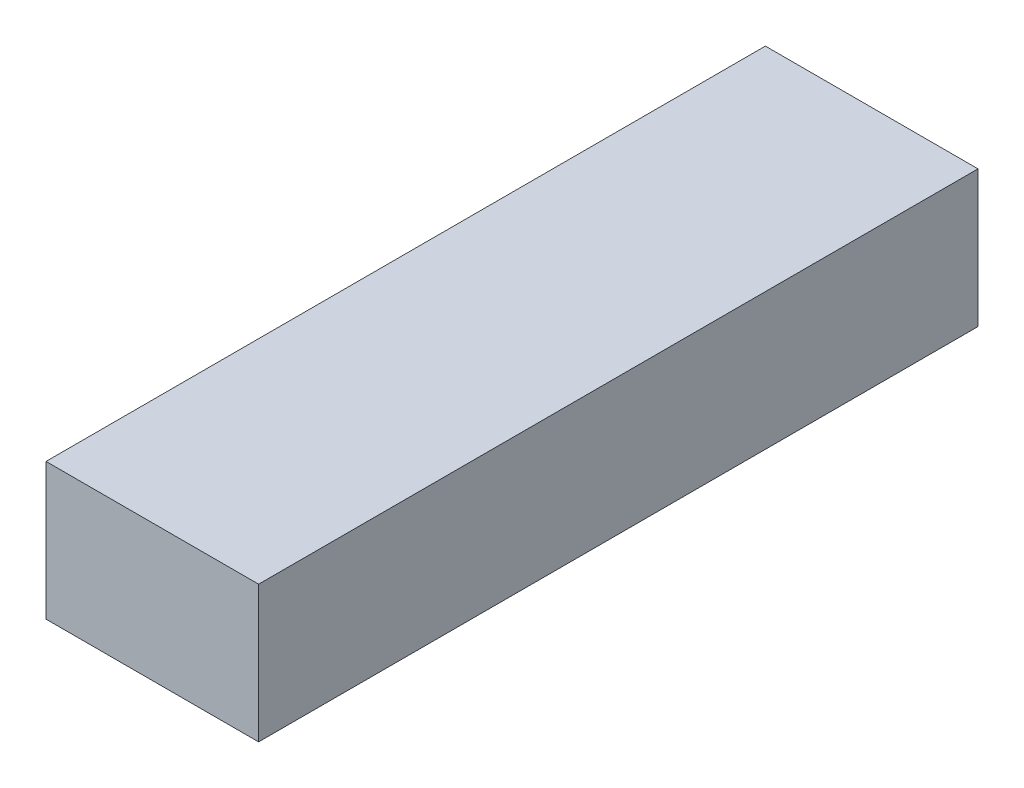
SolidWorks part; units mm, degrees
ref_plane "Front Plane" through (0, 0, 0) normal (0, 0, 1) x (1, 0, 0)
ref_plane "Top Plane" through (0, 0, 0) normal (0, 1, 0) x (1, 0, 0)
ref_plane "Right Plane" through (0, 0, 0) normal (1, 0, 0) x (0, 0, -1)
sketch "Sketch1" plane through (0, 0, 0) normal (0, 0, 1) x (1, 0, 0)
  line L1 (-24.511, 15.748) -> (24.511, 15.748)
  line L2 (-24.511, 15.748) -> (-24.511, -15.748)
  line L3 (-24.511, -15.748) -> (24.511, -15.748)
  line L4 (24.511, 15.748) -> (24.511, -15.748)
  line L5 (-24.511, 15.748) -> (24.511, -15.748) construction
  line L6 (-24.511, -15.748) -> (24.511, 15.748) construction
  point P0 (0, 0)
  dimension "D1" = 31.496
  dimension "D2" = 49.022
extrude "Boss-Extrude1" add sketch "Sketch1" along normal blind 165.862
